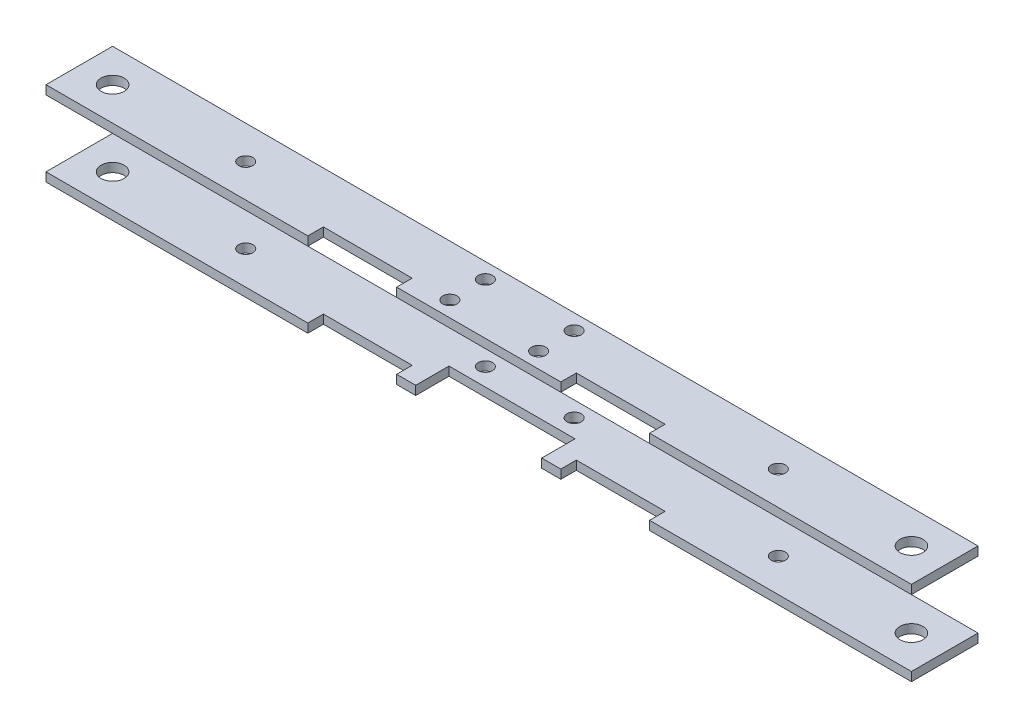
SolidWorks part; units mm, degrees
material "碳板"
ref_plane "前视基准面" through (0, 0, 0) normal (0, 0, 1) x (1, 0, 0)
ref_plane "上视基准面" through (0, 0, 0) normal (0, 1, 0) x (1, 0, 0)
ref_plane "右视基准面" through (0, 0, 0) normal (1, 0, 0) x (0, 0, -1)
ref_plane "基准面1" through (0, 7.5, 0) normal (0, 1, 0) x (1, 0, 0)
sketch "草图1" plane through (0, 7.5, 0) normal (0, 1, 0) x (1, 0, 0)
  line L0 (-107.0759, 0) -> (126.01, 0) construction
  line L1 (-97.5, 7.5) -> (97.5, 7.5)
  line L2 (-97.5, 7.5) -> (-97.5, -7.5)
  line L3 (-97.5, -7.5) -> (97.5, -7.5)
  line L4 (97.5, 7.5) -> (97.5, -7.5)
  line L5 (-97.5, 7.5) -> (97.5, -7.5) construction
  line L6 (-97.5, -7.5) -> (97.5, 7.5) construction
  line L7 (0, 67.3577) -> (0, -42.7651) construction
  line L8 (-38.5, -7.5) -> (-38.5, -4)
  line L9 (-38.5, -4) -> (-18.5, -4)
  line L10 (-18.5, -4) -> (-18.5, -7.5)
  line L11 (-28.5, -4) -> (-28.5, -14.3361) construction
  line L12 (18.5, -4) -> (18.5, -7.5)
  line L13 (38.5, -7.5) -> (38.5, -4)
  line L14 (38.5, -4) -> (18.5, -4)
  circle A0 centre (-90, 0) radius 2.6
  circle A1 centre (-10, 4) radius 1.6
  circle A2 centre (-10, -4) radius 1.6
  circle A3 centre (10, -4) radius 1.6
  circle A4 centre (10, 4) radius 1.6
  circle A5 centre (90, 0) radius 2.6
  circle A6 centre (-60, 0) radius 1.6
  circle A7 centre (60, 0) radius 1.6
  point P0 (0, 0)
  dimension "D3" = 5.2
  dimension "D4" = 3.2
  dimension "D11" = 120
  dimension "D1" = 195
  dimension "D2" = 15
  dimension "D5" = 180
  dimension "D6" = 8
  dimension "D7" = 20
  dimension "D8" = 28.5
  dimension "D9" = 20
  dimension "D10" = 3.5
extrude "凸台-拉伸1" add sketch "草图1" along normal blind 2 contours L14 L13 L3 L4 L1 L2 L8 L9 L10 L12 A4 A3 A0 A1 A2 A5
mirror "镜向3" about plane through (0, 0, 0) normal (0, 1, 0) of bodies 106
sketch "草图2" plane through (0, -7.5, 0) normal (0, 1, 0) x (1, 0, 0)
  line L0 (0, 0) -> (0, -22.6931) construction
  line L1 (-18.5, -7.5) -> (18.5, -7.5) construction
  line L2 (-14.2, 0) -> (14.2, 0)
  line L3 (-14.2, 0) -> (-14.2, -7.5)
  line L4 (-14.2, -7.5) -> (14.2, -7.5)
  line L5 (14.2, 0) -> (14.2, -7.5)
  line L6 (-14.2, 0) -> (14.2, -7.5) construction
  line L7 (-14.2, -7.5) -> (14.2, 0) construction
  point P3 (0, -3.75)
  dimension "D1" = 28.4
  dimension "D2" = 7.5
extrude "切除-拉伸1" cut sketch "草图2" against normal through all
